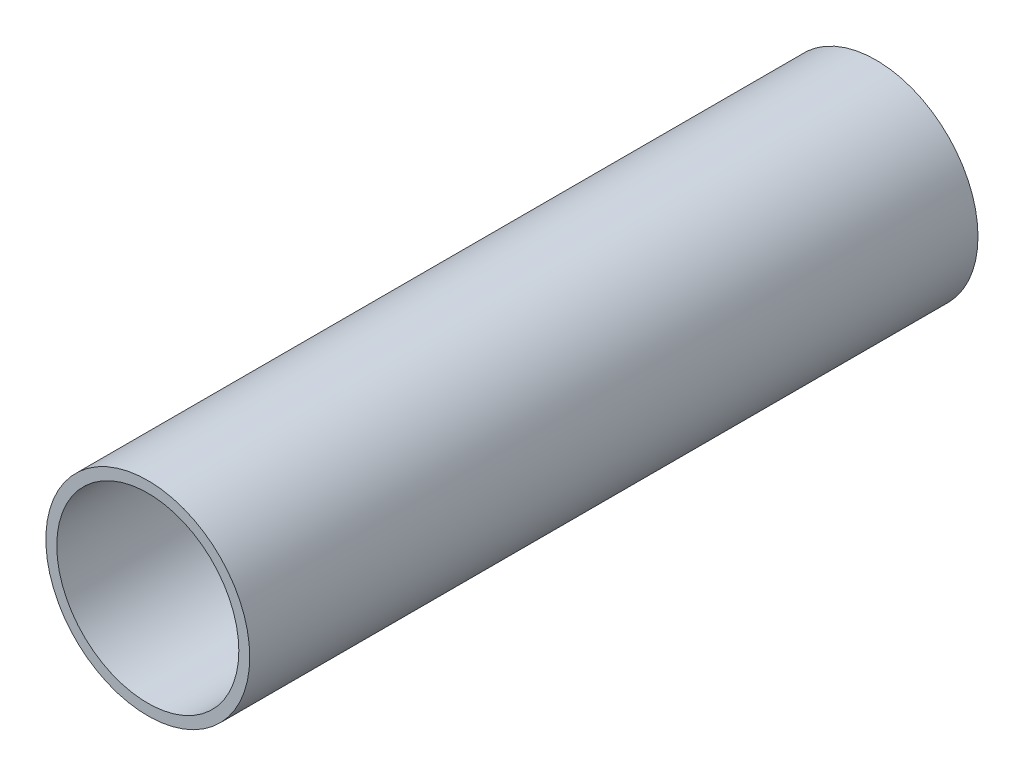
SolidWorks part; units mm, degrees
ref_plane "Front Plane" through (0, 0, 0) normal (0, 0, 1) x (1, 0, 0)
ref_plane "Top Plane" through (0, 0, 0) normal (0, 1, 0) x (1, 0, 0)
ref_plane "Right Plane" through (0, 0, 0) normal (1, 0, 0) x (0, 0, -1)
sketch "Sketch1" plane through (0, 0, 0) normal (0, 0, 1) x (1, 0, 0)
  circle A0 centre (0, 0) radius 31.75
  circle A1 centre (0, 0) radius 35.56
  dimension "D1" = 63.5
  dimension "D2" = 71.12
extrude "Boss-Extrude1" add sketch "Sketch1" along normal blind 254
ref_plane "Plane1" through (0, 0, 127) normal (0, 0, 1) x (1, 0, 0)
